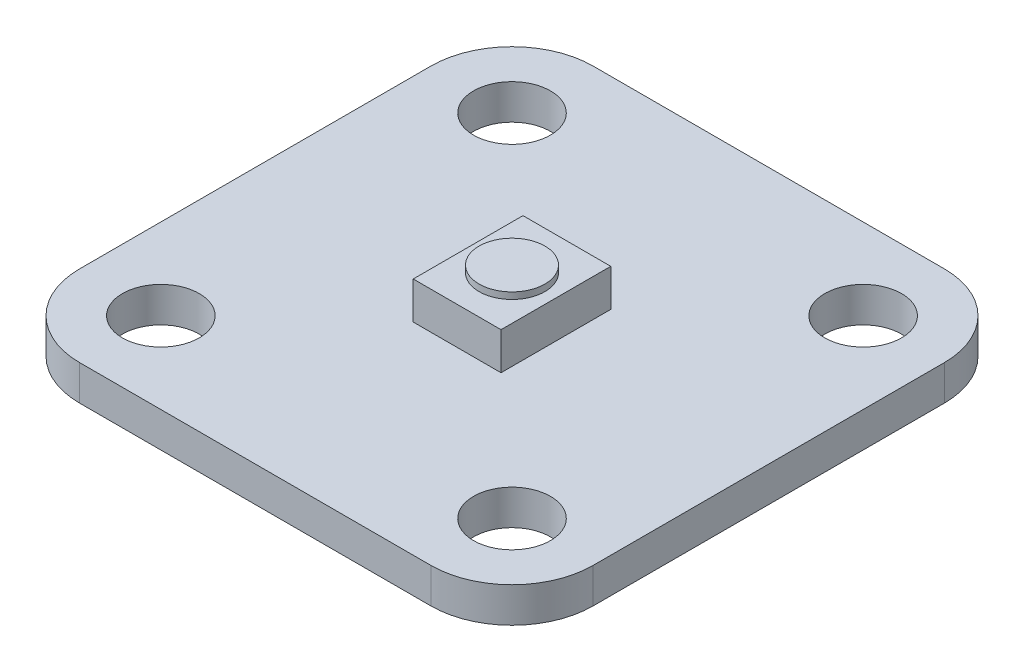
SolidWorks part; units mm, degrees
ref_plane "Front Plane" through (0, 0, 0) normal (0, 0, 1) x (1, 0, 0)
ref_plane "Top Plane" through (0, 0, 0) normal (0, 1, 0) x (1, 0, 0)
ref_plane "Right Plane" through (0, 0, 0) normal (1, 0, 0) x (0, 0, -1)
sketch "Sketch1" plane through (0, 0, 0) normal (0, 1, 0) x (1, 0, 0)
  line L0 (11.7, 19.7) -> (11.7, 23.4) construction
  line L1 (3.7, 0) -> (19.7, 0)
  line L2 (0, 3.7) -> (0, 19.7)
  line L3 (3.7, 23.4) -> (19.7, 23.4)
  line L4 (23.4, 3.7) -> (23.4, 19.7)
  line L5 (3.7, 19.7) -> (19.7, 19.7) construction
  line L6 (3.7, 19.7) -> (3.7, 3.7) construction
  line L7 (3.7, 3.7) -> (19.7, 3.7) construction
  line L8 (19.7, 19.7) -> (19.7, 3.7) construction
  line L9 (19.7, 11.7) -> (23.4, 11.7) construction
  circle A0 centre (3.7, 19.7) radius 1.75
  circle A1 centre (19.7, 19.7) radius 1.75
  circle A2 centre (19.7, 3.7) radius 1.75
  circle A3 centre (3.7, 3.7) radius 1.75
  arc A4 (0, 19.7) -> (3.7, 23.4) centre (3.7, 19.7) cw
  arc A5 (3.7, 0) -> (0, 3.7) centre (3.7, 3.7) cw
  arc A6 (19.7, 0) -> (23.4, 3.7) centre (19.7, 3.7) ccw
  arc A7 (19.7, 23.4) -> (23.4, 19.7) centre (19.7, 19.7) cw
  point P21 (0, 0)
  point P24 (23.4, 0)
  point P27 (23.4, 23.4)
  dimension "D5" = 3.5
  dimension "D6" = 3.5
  dimension "D7" = 3.5
  dimension "D8" = 3.5
  dimension "D9" = 3.7
  dimension "D1" = 23.4
  dimension "D2" = 23.4
  dimension "D3" = 16
  dimension "D4" = 16
extrude "Boss-Extrude1" add sketch "Sketch1" along normal blind 1.6
sketch "Sketch2" plane through (0, 1.6, 0) normal (0, 1, 0) x (1, 0, 0)
  line L0 (11.7, 23.4) -> (11.7, 0)
  line L1 (19.7, 23.4) -> (3.7, 23.4) construction
  line L2 (3.7, 0) -> (19.7, 0) construction
  line L4 (9.7, 9.2) -> (13.7, 9.2)
  line L5 (9.7, 9.2) -> (9.7, 14.2)
  line L6 (9.7, 14.2) -> (13.7, 14.2)
  line L7 (13.7, 9.2) -> (13.7, 14.2)
  line L8 (9.7, 9.2) -> (13.7, 14.2) construction
  line L9 (9.7, 14.2) -> (13.7, 9.2) construction
  point P6 (11.7, 11.7)
  dimension "D1" = 4
  dimension "D2" = 5
extrude "Boss-Extrude2" add sketch "Sketch2" along normal blind 1.7 contours L4 L7 L6 L0 | L6 L5 L4 L0
sketch "Sketch3" plane through (0, 3.3, 0) normal (0, 1, 0) x (1, 0, 0)
  circle A0 centre (11.7, 11.7) radius 1.5
  dimension "D1" = 3
extrude "Boss-Extrude3" add sketch "Sketch3" along normal blind 0.3
